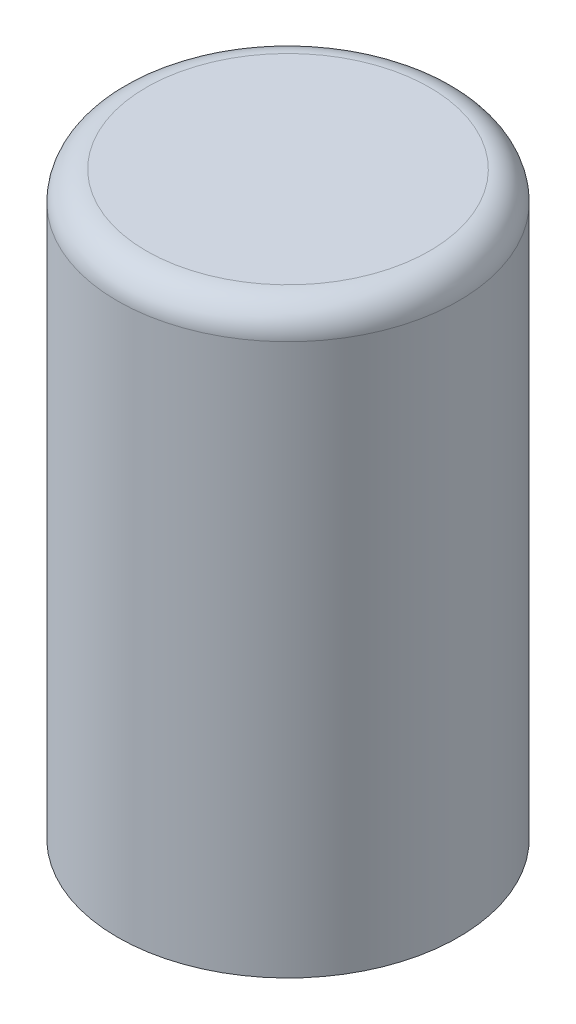
SolidWorks part; units mm, degrees
ref_plane "Front Plane" through (0, 0, 0) normal (0, 0, 1) x (1, 0, 0)
ref_plane "Top Plane" through (0, 0, 0) normal (0, 1, 0) x (1, 0, 0)
ref_plane "Right Plane" through (0, 0, 0) normal (1, 0, 0) x (0, 0, -1)
sketch "Sketch1" plane through (0, 0, 0) normal (0, 1, 0) x (1, 0, 0)
  circle A0 centre (0, 0) radius 15
  dimension "D1" = 30
extrude "Boss-Extrude1" add sketch "Sketch1" along normal blind 51
fillet "Fillet1" radius 2.54 1 edges at (0, 51, 15)
sketch "Sketch2" plane through (0, 0, 0) normal (0, -1, 0) x (1, 0, 0)
  circle A0 centre (0, 0) radius 3.095
  dimension "D1" = 6.19
extrude "Cut-Extrude1" cut sketch "Sketch2" against normal blind 12.7
